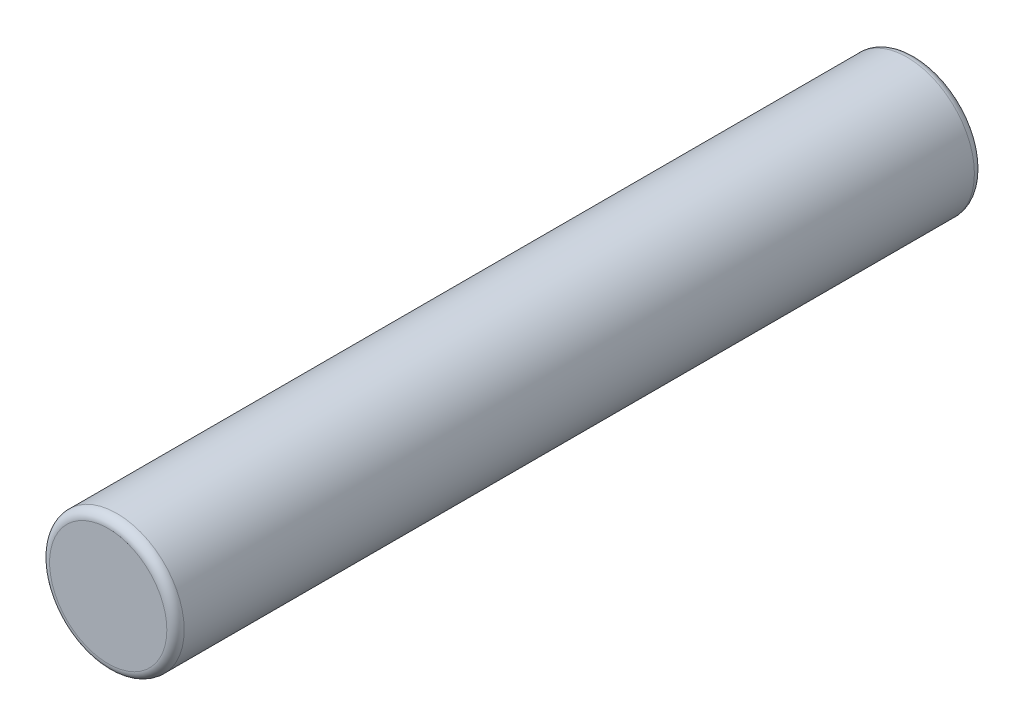
SolidWorks part; units mm, degrees
material "AISI 1020"
ref_plane "Alzado" through (0, 0, 0) normal (0, 0, 1) x (1, 0, 0)
ref_plane "Planta" through (0, 0, 0) normal (0, 1, 0) x (1, 0, 0)
ref_plane "Vista lateral" through (0, 0, 0) normal (1, 0, 0) x (0, 0, -1)
sketch "Croquis1" plane through (0, 0, 0) normal (0, 0, 1) x (1, 0, 0)
  circle A0 centre (0, 0) radius 1.5875
  dimension "D1" = 3.175
extrude "Saliente-Extruir1" add sketch "Croquis1" along normal blind 19.05
fillet "Redondeo1" radius 0.2048 2 edges at (1.5875, 0, 0) (1.5875, 0, 19.05)
